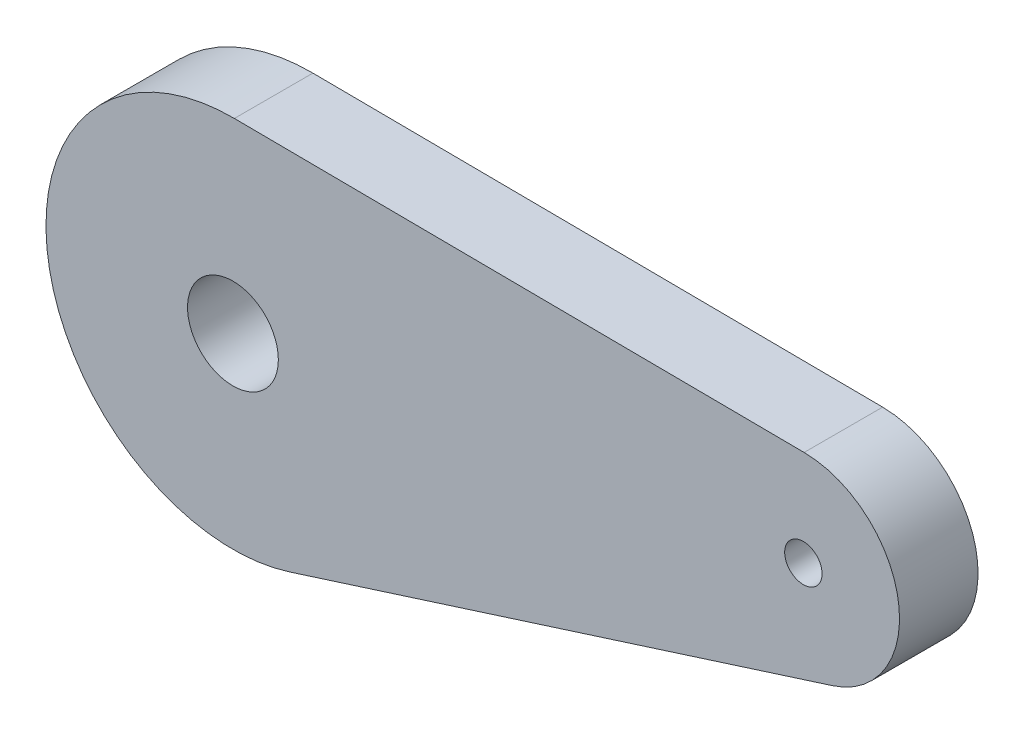
SolidWorks part; units mm, degrees
ref_plane "Front Plane" through (0, 0, 0) normal (0, 0, 1) x (1, 0, 0)
ref_plane "Top Plane" through (0, 0, 0) normal (0, 1, 0) x (1, 0, 0)
ref_plane "Right Plane" through (0, 0, 0) normal (1, 0, 0) x (0, 0, -1)
sketch "Sketch1" plane through (0, 0, 0) normal (0, 0, 1) x (1, 0, 0)
  line L0 (0, 0) -> (0, 28420.5788) construction
  line L1 (0, 0) -> (-28420.5788, 0) construction
  line L2 (-23, 10) -> (-28, 10)
  line L3 (-23, 0) -> (23, 0)
  line L4 (-23, 0) -> (-23, 10)
  line L5 (-23, 10) -> (23, 10)
  line L6 (23, 0) -> (23, 10)
  line L7 (-28, 10) -> (-41.8608, 50.4677)
  line L8 (-24.6313, 80.3256) -> (15.2446, 88.1625)
  line L9 (23, 10) -> (28, 10)
  line L10 (28, 10) -> (39.4051, 19.57)
  line L11 (39.4051, 19.57) -> (39.4051, 38.57)
  line L12 (39.4051, 38.57) -> (22.9346, 83.8223)
  line L13 (-20.22, 57.88) -> (-41.0516, 204.4066) construction
  line L14 (16.5541, 81.5) -> (-4.2776, 228.0266) construction
  line L15 (-75.8246, 230.8844) -> (-41.0516, 204.4066) construction
  line L16 (-41.0516, 204.4066) -> (-4.2776, 228.0266) construction
  line L17 (-4.2776, 228.0266) -> (-75.8246, 230.8844) construction
  line L18 (-75.8246, 230.8844) -> (-226.1828, 176.1814) construction
  line L19 (-204.7956, 140.0346) -> (9.2044, 224.1635) construction
  line L20 (-226.1828, 176.1814) -> (-204.7956, 140.0346) construction
  line L21 (-204.7956, 140.0346) -> (-256.0612, 159.9555) construction
  line L22 (-256.0612, 159.9555) -> (-226.1828, 176.1814) construction
  line L23 (-20.22, 57.88) -> (33.1708, 65.9687)
  line L24 (33.1708, 65.9687) -> (9.2044, 224.1635)
  circle A0 centre (-20.22, 57.88) radius 22.875 construction
  circle A1 centre (16.5541, 81.5) radius 6.79 construction
  arc A2 (-41.8608, 50.4677) -> (-24.6313, 80.3256) centre (-20.22, 57.88) cw
  arc A3 (15.2446, 88.1625) -> (22.9346, 83.8223) centre (16.5541, 81.5) cw
  circle A4 centre (-20.22, 57.88) radius 17.5 construction
  circle A5 centre (16.5541, 81.5) radius 7.5 construction
  circle A6 centre (-41.0516, 204.4066) radius 13.1881 construction
  circle A7 centre (-4.2776, 228.0266) radius 8.7345 construction
  circle A8 centre (-75.8246, 230.8844) radius 8.7345 construction
  circle A9 centre (-226.1828, 176.1814) radius 8.1525 construction
  circle A10 centre (-204.7956, 140.0346) radius 9.1166 construction
  dimension "D7" = 45.75
  dimension "D8" = 13.58
  dimension "D14" = 35
  dimension "D15" = 15
  dimension "D1" = 46
  dimension "D2" = 10
  dimension "D3" = 57.88
  dimension "D4" = 20.22
  dimension "D5" = 16.5541
  dimension "D6" = 81.5
  dimension "D9" = 5
  dimension "D10" = 5
  dimension "D11" = 140
  dimension "D12" = 19
  dimension "D13" = 160
  dimension "D16" = 148
  dimension "D17" = 110
  dimension "D18" = 160
  dimension "D19" = 54
  dimension "D20" = 214
  dimension "D21" = 42
  dimension "D22" = 34
  dimension "D23" = 55
  dimension "D24" = 54
  dimension "D25" = 160
sketch "Sketch3" plane through (0, 0, 0) normal (0, 0, 1) x (1, 0, 0)
  line L0 (-20.22, 57.88) -> (33.1708, 65.9687) construction
  line L1 (-20.22, 57.88) -> (33.1708, 65.9687) construction
  line L2 (-20.0851, 75.3795) -> (33.2401, 74.9684)
  line L3 (35.9028, 57.3933) -> (-14.9078, 41.2058)
  circle A0 centre (-20.22, 57.88) radius 17.5 construction
  circle A1 centre (-20.22, 57.88) radius 17.5
  circle A2 centre (33.1708, 65.9687) radius 9
  circle A3 centre (33.1708, 65.9687) radius 1.75
  circle A4 centre (-20.22, 57.88) radius 4.25
  dimension "D1" = 18
  dimension "D2" = 3.5
  dimension "D3" = 8.5
extrude "Boss-Extrude4" add sketch "Sketch3" along normal mid plane 7.35
